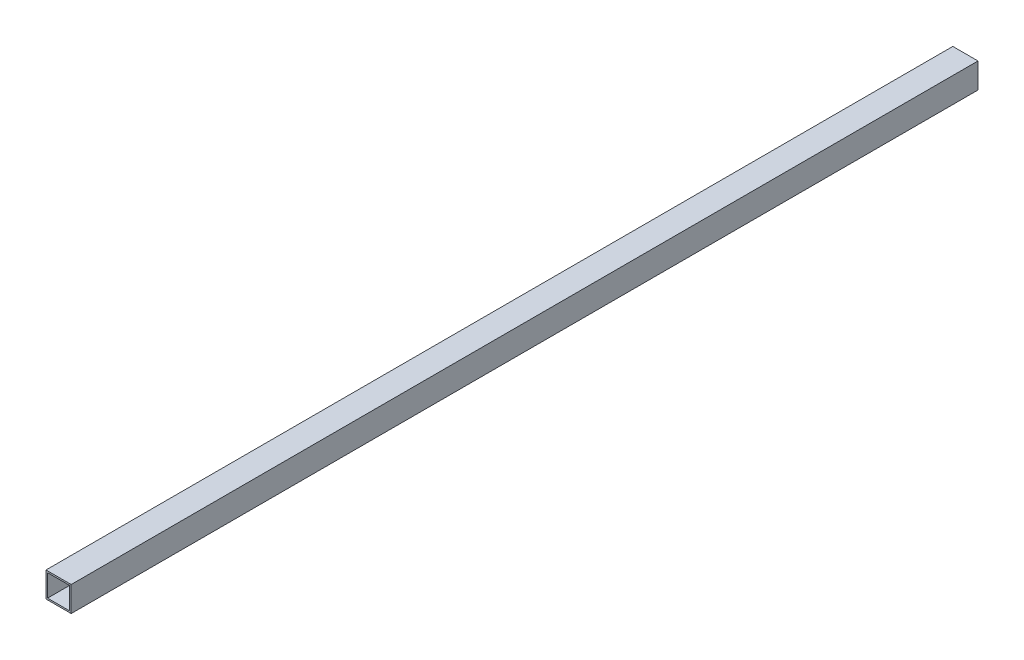
SolidWorks part; units mm, degrees
ref_plane "Front Plane" through (0, 0, 0) normal (0, 0, 1) x (1, 0, 0)
ref_plane "Top Plane" through (0, 0, 0) normal (0, 1, 0) x (1, 0, 0)
ref_plane "Right Plane" through (0, 0, 0) normal (1, 0, 0) x (0, 0, -1)
sketch "Sketch1" plane through (0, 0, 0) normal (0, 0, 1) x (1, 0, 0)
  line L0 (-11.1125, 11.1125) -> (11.1125, 11.1125)
  line L2 (-12.7, 12.7) -> (12.7, 12.7)
  line L3 (-12.7, 12.7) -> (-12.7, -12.7)
  line L4 (-12.7, -12.7) -> (12.7, -12.7)
  line L5 (12.7, 12.7) -> (12.7, -12.7)
  line L10 (11.1125, 11.1125) -> (11.1125, -11.1125)
  line L11 (-11.1125, -11.1125) -> (11.1125, -11.1125)
  line L12 (-11.1125, 11.1125) -> (-11.1125, -11.1125)
  point P12 (0, 12.7)
  point P14 (12.7, 0)
  dimension "Wall Thickness" = 1.5875
  dimension "Outside Width" = 25.4
  dimension "Outside Height" = 25.4
  dimension "Inside Height" = 22.225
  dimension "Inside Width" = 22.225
sketch "Sketch2" plane through (0, 0, 0) normal (1, 0, 0) x (0, 0, -1)
  line L0 (457.2, 0) -> (-457.2, 0)
  point P4 (0, 0)
  point P7 (-457.2, 0)
  point P10 (457.2, 0)
  dimension "Length" = 914.4
sketch "Sketch3" plane through (0, 0, 0) normal (0, 0, 1) x (1, 0, 0)
  line L21 (12.7, 12.7) -> (-12.7, 12.7)
  line L22 (12.7, -12.7) -> (12.7, 12.7)
  line L23 (-12.7, -12.7) -> (12.7, -12.7)
  line L24 (-12.7, 12.7) -> (-12.7, -12.7)
  line L25 (12.7, 12.7) -> (-12.7, 12.7)
  line L26 (12.7, -12.7) -> (12.7, 12.7)
  line L27 (-12.7, -12.7) -> (12.7, -12.7)
  line L28 (-12.7, 12.7) -> (-12.7, -12.7)
  line L29 (11.1125, 11.1125) -> (-11.1125, 11.1125)
  line L30 (11.1125, -11.1125) -> (11.1125, 11.1125)
  line L31 (-11.1125, -11.1125) -> (11.1125, -11.1125)
  line L32 (-11.1125, 11.1125) -> (-11.1125, -11.1125)
  line L33 (11.1125, 11.1125) -> (-11.1125, 11.1125)
  line L34 (11.1125, -11.1125) -> (11.1125, 11.1125)
  line L35 (-11.1125, -11.1125) -> (11.1125, -11.1125)
  line L36 (-11.1125, 11.1125) -> (-11.1125, -11.1125)
  dimension "D1" = 0
  dimension "D2" = 0
extrude "Boss-Extrude1" add sketch "Sketch3" along normal up to vertex (457.2 mm away) and the other way up to vertex (457.2 mm away) up to point (0, 0, 457.2) other way up to point (0, 0, -457.2)
sketch "Drawing Reference" plane through (0, 0, 0) normal (1, 0, 0) x (0, 0, -1)
  line L0 (-457.2, 0) -> (457.2, 0) construction
  line L1 (0, -12.7) -> (0, 12.7) construction
  line L2 (-457.2, -12.7) -> (457.2, -12.7) construction
  line L5 (-457.2, 12.7) -> (457.2, 12.7) construction
  point P7 (-438.912, 0)
  point P8 (438.912, 0)
  dimension "D1" = 18.288
equation "\"D1@Drawing Reference\"=\"Outside Width@Sketch1\" * 0.72"
